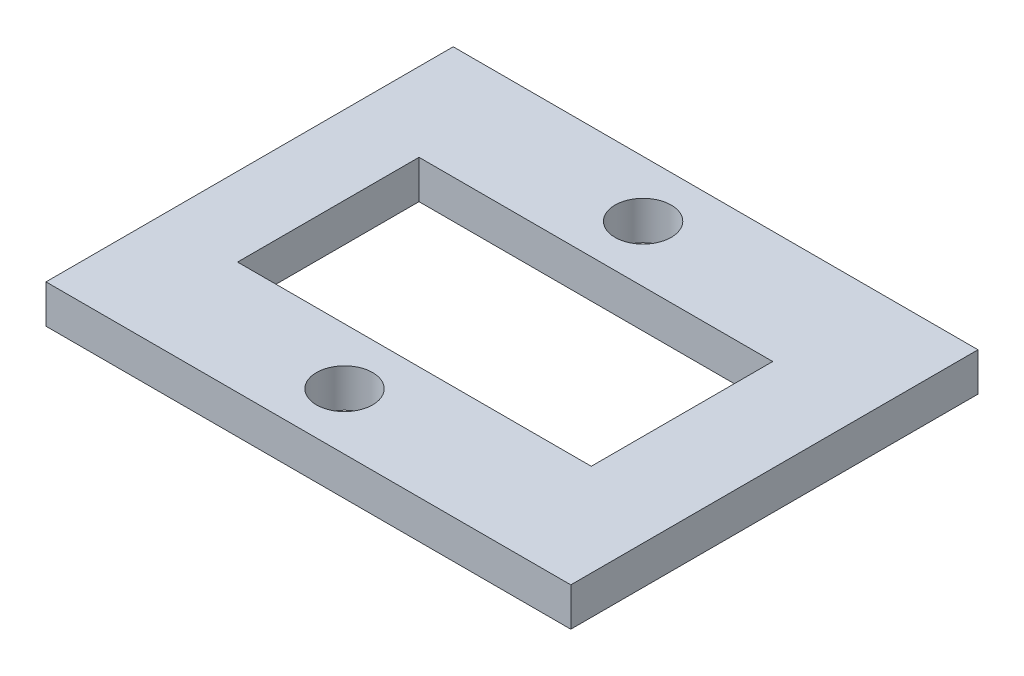
SolidWorks part; units mm, degrees
ref_plane "Front Plane" through (0, 0, 0) normal (0, 0, 1) x (1, 0, 0)
ref_plane "Top Plane" through (0, 0, 0) normal (0, 1, 0) x (1, 0, 0)
ref_plane "Right Plane" through (0, 0, 0) normal (1, 0, 0) x (0, 0, -1)
sketch "Sketch2" plane through (0, 0, 0) normal (0, 1, 0) x (1, 0, 0)
  line L0 (-11.5888, 6.6809) -> (11.4112, 6.6809)
  line L1 (-16.7015, 14.0166) -> (17.4229, 14.0166)
  line L2 (-16.7015, 14.0166) -> (-16.7015, -12.4616)
  line L3 (-16.7015, -12.4616) -> (17.4229, -12.4616)
  line L4 (17.4229, 14.0166) -> (17.4229, -12.4616)
  line L10 (11.4112, -5.1189) -> (-11.5888, -5.1189)
  line L11 (-11.5888, -5.1189) -> (-11.5888, 6.6809)
  line L13 (11.4112, 6.6809) -> (11.4112, -5.1189)
  circle A0 centre (-0.7026, 10.3665) radius 1.825
  circle A1 centre (-0.978, -8.7735) radius 1.825
  dimension "D8" = 3.65
  dimension "D1" = 19.14
  dimension "D2" = 11.7998
  dimension "D4" = 23
extrude "Boss-Extrude1" add sketch "Sketch2" along normal mid plane 2.5
